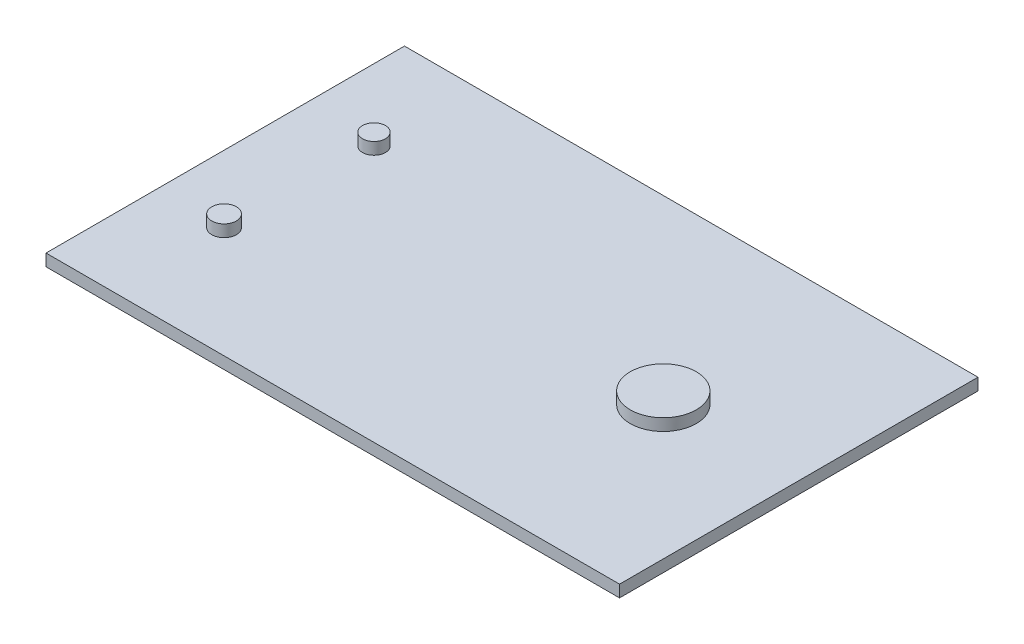
SolidWorks part; units mm, degrees
ref_plane "Front Plane" through (0, 0, 0) normal (0, 0, 1) x (1, 0, 0)
ref_plane "Top Plane" through (0, 0, 0) normal (0, 1, 0) x (1, 0, 0)
ref_plane "Right Plane" through (0, 0, 0) normal (1, 0, 0) x (0, 0, -1)
sketch "Sketch1" plane through (0, 0, 0) normal (0, 1, 0) x (1, 0, 0)
  line L1 (0, 0) -> (60.96, 0)
  line L2 (0, 0) -> (0, 38.1)
  line L3 (0, 38.1) -> (60.96, 38.1)
  line L4 (60.96, 0) -> (60.96, 38.1)
  dimension "D1" = 60.96
  dimension "D2" = 38.1
extrude "Boss-Extrude1" add sketch "Sketch1" along normal blind 1.27
sketch "Sketch4" plane through (0, 1.27, 0) normal (0, 1, 0) x (1, 0, 0)
  circle A0 centre (46.7555, 18.8533) radius 3.5082
extrude "Boss-Extrude3" add sketch "Sketch4" along normal blind 1.27
sketch "Sketch5" plane through (0, 1.27, 0) normal (0, 1, 0) x (1, 0, 0)
  circle A0 centre (7.5738, 27.2872) radius 1.2183
extrude "Boss-Extrude4" add sketch "Sketch5" along normal blind 1.27
sketch "Sketch6" plane through (0, 1.27, 0) normal (0, 1, 0) x (1, 0, 0)
  circle A0 centre (7.1291, 11.7979) radius 1.3068
extrude "Boss-Extrude5" add sketch "Sketch6" along normal blind 1.27
